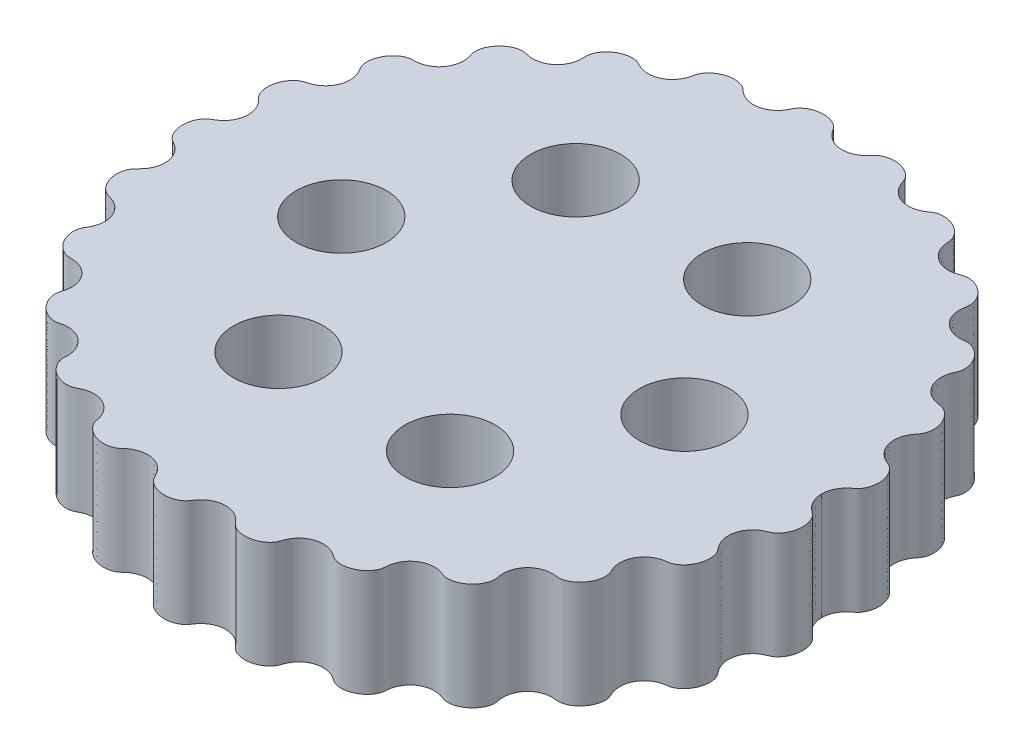
SolidWorks part; units mm, degrees
ref_plane "Front Plane" through (0, 0, 0) normal (0, 0, 1) x (1, 0, 0)
ref_plane "Top Plane" through (0, 0, 0) normal (0, 1, 0) x (1, 0, 0)
ref_plane "Right Plane" through (0, 0, 0) normal (1, 0, 0) x (0, 0, -1)
sketch "Sketch4" plane through (0, 0, 0) normal (0, 1, 0) x (1, 0, 0)
  line L0 (-15.4, 0) -> (14.4, 0) construction
  line L1 (0, 0) -> (0, -14.9128) construction
  line L2 (0, 0) -> (0, 14.9128) construction
  line L3 (-0.5, 0) -> (-0.5, -14.9128) construction
  line L4 (-0.5, 0) -> (-0.5, 14.9128) construction
  line L5 (14.4, 0) -> (15.5, 0) construction
  line L6 (0, 14.9128) -> (0, -14.9128) construction
  line L7 (5.9, 0) -> (9.1, 0) construction
  line L8 (5.9, 0) -> (7.5, 0)
  circle A0 centre (-0.5, 0) radius 16 construction
  circle A1 centre (15.5, 0) radius 1
  circle A2 centre (15.0351, -3.8291) radius 1
  circle A3 centre (13.6673, -7.4356) radius 1
  circle A4 centre (11.4762, -10.61) radius 1
  circle A5 centre (8.589, -13.1677) radius 1
  circle A6 centre (5.1737, -14.9603) radius 1
  circle A7 centre (1.4286, -15.8833) radius 1
  circle A8 centre (-2.4286, -15.8833) radius 1
  circle A9 centre (-6.1737, -14.9603) radius 1
  circle A10 centre (-9.589, -13.1677) radius 1
  circle A11 centre (-12.4762, -10.61) radius 1
  circle A12 centre (-14.6673, -7.4356) radius 1
  circle A13 centre (-16.0351, -3.8291) radius 1
  circle A14 centre (-16.5, 0) radius 1
  circle A15 centre (-16.0351, 3.8291) radius 1
  circle A16 centre (-14.6673, 7.4356) radius 1
  circle A17 centre (-12.4762, 10.61) radius 1
  circle A18 centre (-9.589, 13.1677) radius 1
  circle A19 centre (-6.1737, 14.9603) radius 1
  circle A20 centre (-2.4286, 15.8833) radius 1
  circle A21 centre (1.4286, 15.8833) radius 1
  circle A22 centre (5.1737, 14.9603) radius 1
  circle A23 centre (8.589, 13.1677) radius 1
  circle A24 centre (11.4762, 10.61) radius 1
  circle A25 centre (13.6673, 7.4356) radius 1
  circle A26 centre (15.0351, 3.8291) radius 1
  circle A27 centre (0, 0) radius 8
  circle A28 centre (8, 0) radius 2.1
  circle A29 centre (4, 6.9282) radius 2.1
  circle A30 centre (-4, 6.9282) radius 2.1
  circle A31 centre (-8, 0) radius 2.1
  circle A32 centre (-4, -6.9282) radius 2.1
  circle A33 centre (4, -6.9282) radius 2.1
  circle A34 centre (-1, 0) radius 8 construction
  circle A35 centre (3, -6.9282) radius 2.1
  circle A36 centre (-5, -6.9282) radius 2.1
  circle A37 centre (-9, 0) radius 2.1
  circle A38 centre (-5, 6.9282) radius 2.1
  circle A39 centre (3, 6.9282) radius 2.1
  circle A40 centre (7, 0) radius 2.1
  circle A41 centre (7.5, 0) radius 1.5
  circle A42 centre (3.5, -6.9282) radius 1.5
  circle A43 centre (-4.5, -6.9282) radius 1.5
  circle A44 centre (-8.5, 0) radius 1.5
  circle A45 centre (-4.5, 6.9282) radius 1.5
  circle A46 centre (3.5, 6.9282) radius 1.5
  spline S0 degree 4 poles (14.1521, 3.1658) (14.188, 3.1199) (14.2658, 3.0332) (14.3775, 2.9384) (14.515, 2.8555) (14.6203, 2.806) (14.6874, 2.778) (14.7412, 2.7556) (14.7939, 2.7309) (14.8442, 2.7016) (14.9616, 2.6171) (15.116, 2.4418) (15.2531, 2.163) (15.3044, 1.8261) (15.2781, 1.5454) (15.2134, 1.3341) (15.1457, 1.199) (15.0717, 1.0959) (14.999, 1.0246) (14.9346, 0.9749) (14.8529, 0.9144) (14.7598, 0.8351) (14.6613, 0.7318) (14.5658, 0.5985) (14.4899, 0.4547) (14.4445, 0.3242) (14.4198, 0.2202) (14.4058, 0.1237) (14.3997, 0.036) (14.399, -0.0233) (14.4055, -0.1232) (14.4175, -0.2057) (14.4353, -0.2848) (14.4589, -0.3638) (14.4955, -0.4601) (14.5538, -0.5777) (14.629, -0.6905) (14.7205, -0.7952) (14.8099, -0.8785) (14.886, -0.9397) (14.9653, -0.9969) (15.0394, -1.0608) (15.1018, -1.1365) (15.1543, -1.2193) (15.2086, -1.3292) (15.2563, -1.4688) (15.2881, -1.6381) (15.2945, -1.881) (15.2523, -2.1199) (15.1638, -2.3444) (15.0424, -2.5231) (14.9425, -2.6287) (14.8453, -2.7036) (14.7572, -2.7504) (14.6644, -2.7867) (14.5734, -2.827) (14.4636, -2.8857) (14.309, -2.9902) (14.1305, -3.1658) (13.9721, -3.435) (13.894, -3.7733) (13.9169, -4.0803) (13.9952, -4.3102) (14.0824, -4.4685) (14.1503, -4.5677) (14.21, -4.6429) (14.2706, -4.7176) (14.3202, -4.8002) (14.3654, -4.9109) (14.3993, -5.0496) (14.4169, -5.2624) (14.3843, -5.5009) (14.3041, -5.731) (14.178, -5.9418) (14.0479, -6.0957) (13.9108, -6.2086) (13.7771, -6.2844) (13.6546, -6.3259) (13.5506, -6.3413) (13.4467, -6.3556) (13.3441, -6.3782) (13.2186, -6.4164) (13.0491, -6.4902) (12.8504, -6.6239) (12.6494, -6.8484) (12.5061, -7.1523) (12.463, -7.451) (12.49, -7.6921) (12.5392, -7.8624) (12.5803, -7.968) (12.6183, -8.0504) (12.6544, -8.1336) (12.6783, -8.2214) (12.6929, -8.336) (12.6907, -8.4762) (12.6543, -8.6855) (12.5452, -8.9512) (12.3731, -9.1837) (12.1492, -9.3663) (11.9533, -9.4633) (11.8116, -9.5062) (11.6867, -9.5225) (11.5835, -9.517) (11.4812, -9.5034) (11.3782, -9.4969) (11.2749, -9.4982) (11.1721, -9.508) (11.0085, -9.5382) (10.791, -9.6158) (10.5438, -9.7787) (10.3474, -10.0243) (10.2402, -10.2686) (10.1943, -10.4842) (10.1853, -10.6384) (10.1931, -10.7705) (10.2091, -10.8795) (10.2256, -10.9662) (10.236, -11.0539) (10.2331, -11.1423) (10.2158, -11.2534) (10.1767, -11.3842) (10.0886, -11.5718) (9.9146, -11.8006) (9.6439, -12.0158) (9.3384, -12.1314) (9.0923, -12.1519) (8.9388, -12.1247) (8.8741, -12.1049) (8.8233, -12.0863) (8.76, -12.0622) (8.6577, -12.0268) (8.5127, -11.9913) (8.2954, -11.971) (8.0233, -12.0058) (7.7397, -12.12) (7.4775, -12.3303) (7.3093, -12.5758) (7.2277, -12.7964) (7.1948, -12.9647) (7.1831, -13.0729) (7.1774, -13.16) (7.1639, -13.2682) (7.1207, -13.3961) (7.0432, -13.5357) (6.8963, -13.7154) (6.6678, -13.8963) (6.3478, -14.0387) (6.02, -14.0727) (5.7619, -14.0269) (5.5985, -13.9438) (5.5126, -13.8801) (5.4018, -13.8057) (5.2599, -13.7303) (5.0524, -13.6565) (4.7738, -13.623) (4.4626, -13.6683) (4.1888, -13.7999) (3.9912, -13.9665) (3.8578, -14.1339) (3.7826, -14.2632) (3.7309, -14.3799) (3.6959, -14.48) (3.6689, -14.5606) (3.6251, -14.6573) (3.5494, -14.7647) (3.44, -14.8752) (3.2557, -15.006) (2.9928, -15.1201) (2.6515, -15.1757) (2.3406, -15.1291) (2.1258, -15.0338) (2.011, -14.9468) (1.9698, -14.909) (1.9317, -14.8681) (1.8954, -14.8255) (1.8499, -14.7726) (1.7735, -14.691) (1.6576, -14.5893) (1.4677, -14.4687) (1.2013, -14.3748) (0.8943, -14.3518) (0.5705, -14.4236) (0.3173, -14.5632) (0.1515, -14.7141) (0.0481, -14.8418) (-0.0114, -14.9289) (-0.057, -15.0001) (-0.1205, -15.0845) (-0.2167, -15.1711) (-0.3455, -15.2521) (-0.5484, -15.3356) (-0.8128, -15.3854) (-1.084, -15.3726) (-1.345, -15.2972) (-1.5435, -15.1922) (-1.6658, -15.0976) (-1.7547, -15.002) (-1.8112, -14.9128) (-1.8483, -14.8369) (-1.8948, -14.7422) (-1.9811, -14.5964) (-2.1305, -14.4153) (-2.3717, -14.2374) (-2.6941, -14.1243) (-3.0058, -14.1121) (-3.2798, -14.1742) (-3.4814, -14.2713) (-3.6077, -14.3581) (-3.6929, -14.4296) (-3.7443, -14.4763) (-3.7855, -14.5136) (-3.839, -14.5578) (-3.9718, -14.6426) (-4.2092, -14.7163) (-4.5379, -14.7232) (-4.871, -14.6233) (-5.1192, -14.4741) (-5.2872, -14.3161) (-5.3818, -14.1888) (-5.4416, -14.0686) (-5.4698, -13.9639) (-5.4862, -13.8788) (-5.5106, -13.7734) (-5.5628, -13.6112) (-5.6686, -13.4029) (-5.8615, -13.1808) (-6.1409, -13.0036) (-6.4324, -12.9205) (-6.707, -12.9139) (-6.9246, -12.958) (-7.0705, -13.0119) (-7.1719, -13.0612) (-7.2342, -13.0943) (-7.2842, -13.1203) (-7.3485, -13.1494) (-7.4504, -13.1813) (-7.5929, -13.1993) (-7.8225, -13.1875) (-8.1082, -13.1019) (-8.3607, -12.9481) (-8.5641, -12.7393) (-8.6869, -12.541) (-8.7459, -12.3913) (-8.7711, -12.2579) (-8.7697, -12.1482) (-8.7645, -12.0606) (-8.7633, -11.951) (-8.7731, -11.8212) (-8.8019, -11.6732) (-8.8729, -11.4717) (-9.0045, -11.25) (-9.2205, -11.0351) (-9.4997, -10.8905) (-9.7475, -10.8369) (-9.9383, -10.8322) (-10.0675, -10.8437) (-10.1698, -10.8609) (-10.2704, -10.8859) (-10.3717, -10.9089) (-10.4995, -10.9144) (-10.6499, -10.893) (-10.8644, -10.8236) (-11.1154, -10.6702) (-11.3185, -10.4608) (-11.4614, -10.2119) (-11.5248, -10.0134) (-11.5464, -9.8777) (-11.5487, -9.7646) (-11.5393, -9.6761) (-11.5169, -9.5902) (-11.4896, -9.5058) (-11.4606, -9.3988) (-11.4371, -9.2678) (-11.428, -9.1126) (-11.4489, -8.8917) (-11.5253, -8.6444) (-11.6806, -8.3917) (-11.9083, -8.1893) (-12.1461, -8.0664) (-12.3515, -8.0112) (-12.509, -7.9918) (-12.6408, -7.9895) (-12.7466, -7.9882) (-12.8744, -7.9638) (-13.0178, -7.9059) (-13.1692, -7.8114) (-13.319, -7.6747) (-13.472, -7.4805) (-13.5815, -7.2609) (-13.644, -7.0266) (-13.6529, -6.8129) (-13.6365, -6.6729) (-13.6064, -6.5605) (-13.5704, -6.4764) (-13.5232, -6.3982) (-13.4752, -6.3206) (-13.4215, -6.2199) (-13.3522, -6.0556) (-13.2972, -5.8178) (-13.3061, -5.5112) (-13.4183, -5.1858) (-13.5996, -4.9373) (-13.7884, -4.7826) (-13.9504, -4.6931) (-14.068, -4.6441) (-14.1647, -4.6121) (-14.2634, -4.587) (-14.3606, -4.5562) (-14.4721, -4.4972) (-14.5906, -4.4054) (-14.7415, -4.2409) (-14.8856, -3.984) (-14.9605, -3.7) (-14.9625, -3.4094) (-14.9171, -3.1994) (-14.8649, -3.0656) (-14.8048, -2.9613) (-14.7437, -2.886) (-14.6735, -2.8194) (-14.6048, -2.7515) (-14.5411, -2.6786) (-14.4829, -2.6013) (-14.3984, -2.4684) (-14.3099, -2.2678) (-14.2572, -1.9916) (-14.2948, -1.6527) (-14.4157, -1.3725) (-14.5648, -1.1806) (-14.7009, -1.0585) (-14.8015, -0.9857) (-14.886, -0.9336) (-14.9732, -0.8861) (-15.056, -0.8309) (-15.1453, -0.7457) (-15.2341, -0.6279) (-15.3021, -0.4979) (-15.3506, -0.3595) (-15.3784, -0.2422) (-15.3932, -0.1473) (-15.4005, -0.038) (-15.4007, 0.0312) (-15.3943, 0.133) (-15.3819, 0.2227) (-15.3632, 0.3082) (-15.3383, 0.3938) (-15.2991, 0.498) (-15.241, 0.614) (-15.1569, 0.7356) (-15.0521, 0.8388) (-14.947, 0.9) (-14.8417, 0.9596) (-14.7374, 1.0292) (-14.6222, 1.1253) (-14.4762, 1.2888) (-14.3483, 1.5104) (-14.2696, 1.788) (-14.2718, 2.0824) (-14.3338, 2.3297) (-14.4228, 2.5131) (-14.5089, 2.6398) (-14.5912, 2.7371) (-14.6628, 2.8095) (-14.7315, 2.8736) (-14.7874, 2.9388) (-14.8392, 3.0187) (-14.9, 3.1445) (-14.933, 3.2628) (-14.9484, 3.3663) (-14.9531, 3.4358) knots 0 0 0 0 0 0.003662 0.007324 0.009155 0.010071 0.010986 0.011902 0.012818 0.013733 0.014649 0.020984 0.02732 0.032959 0.035778 0.038598 0.041156 0.042436 0.043715 0.044995 0.046274 0.048833 0.051398 0.053964 0.05653 0.059096 0.059963 0.060831 0.062566 0.06386 0.065154 0.066448 0.067743 0.069037 0.070331 0.072919 0.075992 0.077529 0.079065 0.080602 0.082139 0.083675 0.085212 0.086754 0.088296 0.09138 0.094464 0.097548 0.103529 0.106519 0.10951 0.111075 0.112641 0.114207 0.115773 0.117339 0.118905 0.122036 0.127492 0.132948 0.138255 0.143562 0.146585 0.148096 0.149608 0.151119 0.15263 0.154142 0.155653 0.158618 0.161583 0.167513 0.170668 0.173824 0.176979 0.180135 0.181785 0.183435 0.185086 0.186736 0.188387 0.190037 0.193338 0.198334 0.203329 0.208757 0.214186 0.217039 0.218465 0.219892 0.221319 0.222745 0.224172 0.225598 0.228568 0.231538 0.237477 0.243509 0.246525 0.249541 0.251164 0.252787 0.25441 0.256033 0.257656 0.259279 0.260902 0.262525 0.268116 0.273708 0.279232 0.281995 0.284757 0.287531 0.288919 0.290306 0.291693 0.293081 0.294468 0.295855 0.298752 0.301648 0.307441 0.313806 0.320171 0.321875 0.322726 0.323578 0.32443 0.325282 0.326985 0.330392 0.333799 0.338942 0.344084 0.349371 0.354658 0.3574 0.358771 0.360142 0.361513 0.362884 0.365627 0.368572 0.371516 0.377406 0.383828 0.390249 0.39193 0.393611 0.395291 0.396972 0.400333 0.403695 0.409076 0.414457 0.419833 0.422521 0.425209 0.427878 0.429213 0.430548 0.431883 0.433218 0.435887 0.438758 0.441629 0.44737 0.453781 0.460191 0.46107 0.46195 0.462829 0.463708 0.464587 0.465466 0.467225 0.470742 0.474259 0.479542 0.484825 0.489836 0.494847 0.497504 0.498832 0.500161 0.501489 0.502818 0.505475 0.508247 0.51102 0.516564 0.52227 0.525123 0.527976 0.530631 0.531959 0.533286 0.534614 0.535941 0.538597 0.543936 0.549276 0.554531 0.559787 0.563284 0.566782 0.568531 0.569405 0.570279 0.571154 0.572028 0.573777 0.580153 0.586529 0.592383 0.595311 0.598238 0.600963 0.602326 0.603688 0.605051 0.606414 0.609139 0.614393 0.619646 0.62466 0.629675 0.633224 0.636772 0.638547 0.639434 0.640321 0.641208 0.642095 0.64387 0.647026 0.650182 0.656494 0.66242 0.665383 0.668345 0.671105 0.672484 0.673864 0.675243 0.676623 0.679382 0.682041 0.684701 0.690021 0.695473 0.700926 0.704188 0.705819 0.70745 0.709081 0.710712 0.712344 0.713975 0.717095 0.720216 0.726458 0.732287 0.735201 0.738116 0.739511 0.740907 0.742302 0.743698 0.745093 0.746488 0.749279 0.752059 0.754839 0.760398 0.765424 0.770449 0.773769 0.777088 0.778748 0.780408 0.782068 0.783727 0.786901 0.790075 0.793249 0.796422 0.802397 0.805385 0.808372 0.809808 0.811244 0.812679 0.814115 0.81555 0.816986 0.819857 0.825318 0.830779 0.83599 0.841201 0.844404 0.846006 0.847607 0.849209 0.850811 0.852412 0.854014 0.857107 0.8602 0.866387 0.872353 0.875336 0.878319 0.87984 0.881361 0.882882 0.884402 0.885923 0.887444 0.888965 0.890486 0.895823 0.90116 0.906397 0.911634 0.914757 0.916319 0.91788 0.919441 0.921003 0.922564 0.924126 0.927182 0.930238 0.931767 0.933295 0.934823 0.936351 0.937751 0.93915 0.940549 0.941949 0.943348 0.944747 0.947546 0.950087 0.952628 0.953898 0.955168 0.957709 0.960509 0.96331 0.96891 0.973663 0.978415 0.981621 0.984826 0.986428 0.988031 0.989634 0.991236 0.992332 0.993427 0.995618 1 1 1 1 1 construction
  spline S1 degree 4 poles (14.4, 0) (14.4, -0.018) (14.401, -0.0542) (14.4055, -0.1232) (14.4175, -0.2057) (14.4353, -0.2848) (14.4589, -0.3638) (14.4955, -0.4601) (14.5538, -0.5777) (14.629, -0.6905) (14.7205, -0.7952) (14.8099, -0.8785) (14.886, -0.9397) (14.9653, -0.9969) (15.0394, -1.0608) (15.1018, -1.1365) (15.1543, -1.2193) (15.2086, -1.3292) (15.2563, -1.4688) (15.2881, -1.6381) (15.2945, -1.881) (15.2523, -2.1199) (15.1638, -2.3444) (15.0424, -2.5231) (14.9425, -2.6287) (14.8453, -2.7036) (14.7572, -2.7504) (14.6644, -2.7867) (14.5734, -2.827) (14.4636, -2.8857) (14.309, -2.9902) (14.1305, -3.1658) (13.9721, -3.435) (13.894, -3.7733) (13.9169, -4.0803) (13.9952, -4.3102) (14.0824, -4.4685) (14.1503, -4.5677) (14.21, -4.6429) (14.2706, -4.7176) (14.3202, -4.8002) (14.3654, -4.9109) (14.3993, -5.0496) (14.4169, -5.2624) (14.3843, -5.5009) (14.3041, -5.731) (14.178, -5.9418) (14.0479, -6.0957) (13.9108, -6.2086) (13.7771, -6.2844) (13.6546, -6.3259) (13.5506, -6.3413) (13.4467, -6.3556) (13.3441, -6.3782) (13.2186, -6.4164) (13.0491, -6.4902) (12.8504, -6.6239) (12.6494, -6.8484) (12.5061, -7.1523) (12.463, -7.451) (12.49, -7.6921) (12.5392, -7.8624) (12.5803, -7.968) (12.6183, -8.0504) (12.6544, -8.1336) (12.6783, -8.2214) (12.6929, -8.336) (12.6907, -8.4762) (12.6543, -8.6855) (12.5452, -8.9512) (12.3731, -9.1837) (12.1492, -9.3663) (11.9533, -9.4633) (11.8116, -9.5062) (11.6867, -9.5225) (11.5835, -9.517) (11.4812, -9.5034) (11.3782, -9.4969) (11.2749, -9.4982) (11.1721, -9.508) (11.0085, -9.5382) (10.791, -9.6158) (10.5438, -9.7787) (10.3474, -10.0243) (10.2402, -10.2686) (10.1943, -10.4842) (10.1853, -10.6384) (10.1931, -10.7705) (10.2091, -10.8795) (10.2256, -10.9662) (10.236, -11.0539) (10.2331, -11.1423) (10.2158, -11.2534) (10.1767, -11.3842) (10.0886, -11.5718) (9.9146, -11.8006) (9.6439, -12.0158) (9.3384, -12.1314) (9.0923, -12.1519) (8.9388, -12.1247) (8.8741, -12.1049) (8.8233, -12.0863) (8.76, -12.0622) (8.6577, -12.0268) (8.5127, -11.9913) (8.2954, -11.971) (8.0233, -12.0058) (7.7397, -12.12) (7.4775, -12.3303) (7.3093, -12.5758) (7.2277, -12.7964) (7.1948, -12.9647) (7.1831, -13.0729) (7.1774, -13.16) (7.1639, -13.2682) (7.1207, -13.3961) (7.0432, -13.5357) (6.8963, -13.7154) (6.6678, -13.8963) (6.3478, -14.0387) (6.02, -14.0727) (5.7619, -14.0269) (5.5985, -13.9438) (5.5126, -13.8801) (5.4018, -13.8057) (5.2599, -13.7303) (5.0524, -13.6565) (4.7738, -13.623) (4.4626, -13.6683) (4.1888, -13.7999) (3.9912, -13.9665) (3.8578, -14.1339) (3.7826, -14.2632) (3.7309, -14.3799) (3.6959, -14.48) (3.6689, -14.5606) (3.6251, -14.6573) (3.5494, -14.7647) (3.44, -14.8752) (3.2557, -15.006) (2.9928, -15.1201) (2.6515, -15.1757) (2.3406, -15.1291) (2.1258, -15.0338) (2.011, -14.9468) (1.9698, -14.909) (1.9317, -14.8681) (1.8954, -14.8255) (1.8499, -14.7726) (1.7735, -14.691) (1.6576, -14.5893) (1.4677, -14.4687) (1.2013, -14.3748) (0.8943, -14.3518) (0.5705, -14.4236) (0.3173, -14.5632) (0.1515, -14.7141) (0.0481, -14.8418) (-0.0114, -14.9289) (-0.057, -15.0001) (-0.1205, -15.0845) (-0.2167, -15.1711) (-0.3455, -15.2521) (-0.5484, -15.3356) (-0.8128, -15.3854) (-1.084, -15.3726) (-1.345, -15.2972) (-1.5435, -15.1922) (-1.6658, -15.0976) (-1.7547, -15.002) (-1.8112, -14.9128) (-1.8483, -14.8369) (-1.8948, -14.7422) (-1.9811, -14.5964) (-2.1305, -14.4153) (-2.3717, -14.2374) (-2.6941, -14.1243) (-3.0058, -14.1121) (-3.2798, -14.1742) (-3.4814, -14.2713) (-3.6077, -14.3581) (-3.6929, -14.4296) (-3.7443, -14.4763) (-3.7855, -14.5136) (-3.839, -14.5578) (-3.9718, -14.6426) (-4.2092, -14.7163) (-4.5379, -14.7232) (-4.871, -14.6233) (-5.1192, -14.4741) (-5.2872, -14.3161) (-5.3818, -14.1888) (-5.4416, -14.0686) (-5.4698, -13.9639) (-5.4862, -13.8788) (-5.5106, -13.7734) (-5.5628, -13.6112) (-5.6686, -13.4029) (-5.8615, -13.1808) (-6.1409, -13.0036) (-6.4324, -12.9205) (-6.707, -12.9139) (-6.9246, -12.958) (-7.0705, -13.0119) (-7.1719, -13.0612) (-7.2342, -13.0943) (-7.2842, -13.1203) (-7.3485, -13.1494) (-7.4504, -13.1813) (-7.5929, -13.1993) (-7.8225, -13.1875) (-8.1082, -13.1019) (-8.3607, -12.9481) (-8.5641, -12.7393) (-8.6869, -12.541) (-8.7459, -12.3913) (-8.7711, -12.2579) (-8.7697, -12.1482) (-8.7645, -12.0606) (-8.7633, -11.951) (-8.7731, -11.8212) (-8.8019, -11.6732) (-8.8729, -11.4717) (-9.0045, -11.25) (-9.2205, -11.0351) (-9.4997, -10.8905) (-9.7475, -10.8369) (-9.9383, -10.8322) (-10.0675, -10.8437) (-10.1698, -10.8609) (-10.2704, -10.8859) (-10.3717, -10.9089) (-10.4995, -10.9144) (-10.6499, -10.893) (-10.8644, -10.8236) (-11.1154, -10.6702) (-11.3185, -10.4608) (-11.4614, -10.2119) (-11.5248, -10.0134) (-11.5464, -9.8777) (-11.5487, -9.7646) (-11.5393, -9.6761) (-11.5169, -9.5902) (-11.4896, -9.5058) (-11.4606, -9.3988) (-11.4371, -9.2678) (-11.428, -9.1126) (-11.4489, -8.8917) (-11.5253, -8.6444) (-11.6806, -8.3917) (-11.9083, -8.1893) (-12.1461, -8.0664) (-12.3515, -8.0112) (-12.509, -7.9918) (-12.6408, -7.9895) (-12.7466, -7.9882) (-12.8744, -7.9638) (-13.0178, -7.9059) (-13.1692, -7.8114) (-13.319, -7.6747) (-13.472, -7.4805) (-13.5815, -7.2609) (-13.644, -7.0266) (-13.6529, -6.8129) (-13.6365, -6.6729) (-13.6064, -6.5605) (-13.5704, -6.4764) (-13.5232, -6.3982) (-13.4752, -6.3206) (-13.4215, -6.2199) (-13.3522, -6.0556) (-13.2972, -5.8178) (-13.3061, -5.5112) (-13.4183, -5.1858) (-13.5996, -4.9373) (-13.7884, -4.7826) (-13.9504, -4.6931) (-14.068, -4.6441) (-14.1647, -4.6121) (-14.2634, -4.587) (-14.3606, -4.5562) (-14.4721, -4.4972) (-14.5906, -4.4054) (-14.7415, -4.2409) (-14.8856, -3.984) (-14.9605, -3.7) (-14.9625, -3.4094) (-14.9171, -3.1994) (-14.8649, -3.0656) (-14.8048, -2.9613) (-14.7437, -2.886) (-14.6735, -2.8194) (-14.6048, -2.7515) (-14.5411, -2.6786) (-14.4829, -2.6013) (-14.3984, -2.4684) (-14.3099, -2.2678) (-14.2572, -1.9916) (-14.2948, -1.6527) (-14.4157, -1.3725) (-14.5648, -1.1806) (-14.7009, -1.0585) (-14.8015, -0.9857) (-14.886, -0.9336) (-14.9732, -0.8861) (-15.056, -0.8309) (-15.1453, -0.7457) (-15.2341, -0.6279) (-15.3021, -0.4979) (-15.3506, -0.3595) (-15.3784, -0.2422) (-15.3932, -0.1473) (-15.3988, -0.0635) (-15.4, -0.0212) (-15.4, 0) knots 0.062566 0.062566 0.062566 0.062566 0.062566 0.06386 0.065154 0.066448 0.067743 0.069037 0.070331 0.072919 0.075992 0.077529 0.079065 0.080602 0.082139 0.083675 0.085212 0.086754 0.088296 0.09138 0.094464 0.097548 0.103529 0.106519 0.10951 0.111075 0.112641 0.114207 0.115773 0.117339 0.118905 0.122036 0.127492 0.132948 0.138255 0.143562 0.146585 0.148096 0.149608 0.151119 0.15263 0.154142 0.155653 0.158618 0.161583 0.167513 0.170668 0.173824 0.176979 0.180135 0.181785 0.183435 0.185086 0.186736 0.188387 0.190037 0.193338 0.198334 0.203329 0.208757 0.214186 0.217039 0.218465 0.219892 0.221319 0.222745 0.224172 0.225598 0.228568 0.231538 0.237477 0.243509 0.246525 0.249541 0.251164 0.252787 0.25441 0.256033 0.257656 0.259279 0.260902 0.262525 0.268116 0.273708 0.279232 0.281995 0.284757 0.287531 0.288919 0.290306 0.291693 0.293081 0.294468 0.295855 0.298752 0.301648 0.307441 0.313806 0.320171 0.321875 0.322726 0.323578 0.32443 0.325282 0.326985 0.330392 0.333799 0.338942 0.344084 0.349371 0.354658 0.3574 0.358771 0.360142 0.361513 0.362884 0.365627 0.368572 0.371516 0.377406 0.383828 0.390249 0.39193 0.393611 0.395291 0.396972 0.400333 0.403695 0.409076 0.414457 0.419833 0.422521 0.425209 0.427878 0.429213 0.430548 0.431883 0.433218 0.435887 0.438758 0.441629 0.44737 0.453781 0.460191 0.46107 0.46195 0.462829 0.463708 0.464587 0.465466 0.467225 0.470742 0.474259 0.479542 0.484825 0.489836 0.494847 0.497504 0.498832 0.500161 0.501489 0.502818 0.505475 0.508247 0.51102 0.516564 0.52227 0.525123 0.527976 0.530631 0.531959 0.533286 0.534614 0.535941 0.538597 0.543936 0.549276 0.554531 0.559787 0.563284 0.566782 0.568531 0.569405 0.570279 0.571154 0.572028 0.573777 0.580153 0.586529 0.592383 0.595311 0.598238 0.600963 0.602326 0.603688 0.605051 0.606414 0.609139 0.614393 0.619646 0.62466 0.629675 0.633224 0.636772 0.638547 0.639434 0.640321 0.641208 0.642095 0.64387 0.647026 0.650182 0.656494 0.66242 0.665383 0.668345 0.671105 0.672484 0.673864 0.675243 0.676623 0.679382 0.682041 0.684701 0.690021 0.695473 0.700926 0.704188 0.705819 0.70745 0.709081 0.710712 0.712344 0.713975 0.717095 0.720216 0.726458 0.732287 0.735201 0.738116 0.739511 0.740907 0.742302 0.743698 0.745093 0.746488 0.749279 0.752059 0.754839 0.760398 0.765424 0.770449 0.773769 0.777088 0.778748 0.780408 0.782068 0.783727 0.786901 0.790075 0.793249 0.796422 0.802397 0.805385 0.808372 0.809808 0.811244 0.812679 0.814115 0.81555 0.816986 0.819857 0.825318 0.830779 0.83599 0.841201 0.844404 0.846006 0.847607 0.849209 0.850811 0.852412 0.854014 0.857107 0.8602 0.866387 0.872353 0.875336 0.878319 0.87984 0.881361 0.882882 0.884402 0.885923 0.887444 0.888965 0.890486 0.895823 0.90116 0.906397 0.911634 0.914757 0.916319 0.91788 0.919441 0.921003 0.922564 0.924126 0.927182 0.930238 0.931767 0.933295 0.934823 0.936351 0.936351 0.936351 0.936351 0.936351
  spline S2 degree 4 poles (14.4, 0) (14.4, 0.018) (14.401, 0.0542) (14.4055, 0.1232) (14.4175, 0.2057) (14.4353, 0.2848) (14.4589, 0.3638) (14.4955, 0.4601) (14.5538, 0.5777) (14.629, 0.6905) (14.7205, 0.7952) (14.8099, 0.8785) (14.886, 0.9397) (14.9653, 0.9969) (15.0394, 1.0608) (15.1018, 1.1365) (15.1543, 1.2193) (15.2086, 1.3292) (15.2563, 1.4688) (15.2881, 1.6381) (15.2945, 1.881) (15.2523, 2.1199) (15.1638, 2.3444) (15.0424, 2.5231) (14.9425, 2.6287) (14.8453, 2.7036) (14.7572, 2.7504) (14.6644, 2.7867) (14.5734, 2.827) (14.4636, 2.8857) (14.309, 2.9902) (14.1305, 3.1658) (13.9721, 3.435) (13.894, 3.7733) (13.9169, 4.0803) (13.9952, 4.3102) (14.0824, 4.4685) (14.1503, 4.5677) (14.21, 4.6429) (14.2706, 4.7176) (14.3202, 4.8002) (14.3654, 4.9109) (14.3993, 5.0496) (14.4169, 5.2624) (14.3843, 5.5009) (14.3041, 5.731) (14.178, 5.9418) (14.0479, 6.0957) (13.9108, 6.2086) (13.7771, 6.2844) (13.6546, 6.3259) (13.5506, 6.3413) (13.4467, 6.3556) (13.3441, 6.3782) (13.2186, 6.4164) (13.0491, 6.4902) (12.8504, 6.6239) (12.6494, 6.8484) (12.5061, 7.1523) (12.463, 7.451) (12.49, 7.6921) (12.5392, 7.8624) (12.5803, 7.968) (12.6183, 8.0504) (12.6544, 8.1336) (12.6783, 8.2214) (12.6929, 8.336) (12.6907, 8.4762) (12.6543, 8.6855) (12.5452, 8.9512) (12.3731, 9.1837) (12.1492, 9.3663) (11.9533, 9.4633) (11.8116, 9.5062) (11.6867, 9.5225) (11.5835, 9.517) (11.4812, 9.5034) (11.3782, 9.4969) (11.2749, 9.4982) (11.1721, 9.508) (11.0085, 9.5382) (10.791, 9.6158) (10.5438, 9.7787) (10.3474, 10.0243) (10.2402, 10.2686) (10.1943, 10.4842) (10.1853, 10.6384) (10.1931, 10.7705) (10.2091, 10.8795) (10.2256, 10.9662) (10.236, 11.0539) (10.2331, 11.1423) (10.2158, 11.2534) (10.1767, 11.3842) (10.0886, 11.5718) (9.9146, 11.8006) (9.6439, 12.0158) (9.3384, 12.1314) (9.0923, 12.1519) (8.9388, 12.1247) (8.8741, 12.1049) (8.8233, 12.0863) (8.76, 12.0622) (8.6577, 12.0268) (8.5127, 11.9913) (8.2954, 11.971) (8.0233, 12.0058) (7.7397, 12.12) (7.4775, 12.3303) (7.3093, 12.5758) (7.2277, 12.7964) (7.1948, 12.9647) (7.1831, 13.0729) (7.1774, 13.16) (7.1639, 13.2682) (7.1207, 13.3961) (7.0432, 13.5357) (6.8963, 13.7154) (6.6678, 13.8963) (6.3478, 14.0387) (6.02, 14.0727) (5.7619, 14.0269) (5.5985, 13.9438) (5.5126, 13.8801) (5.4018, 13.8057) (5.2599, 13.7303) (5.0524, 13.6565) (4.7738, 13.623) (4.4626, 13.6683) (4.1888, 13.7999) (3.9912, 13.9665) (3.8578, 14.1339) (3.7826, 14.2632) (3.7309, 14.3799) (3.6959, 14.48) (3.6689, 14.5606) (3.6251, 14.6573) (3.5494, 14.7647) (3.44, 14.8752) (3.2557, 15.006) (2.9928, 15.1201) (2.6515, 15.1757) (2.3406, 15.1291) (2.1258, 15.0338) (2.011, 14.9468) (1.9698, 14.909) (1.9317, 14.8681) (1.8954, 14.8255) (1.8499, 14.7726) (1.7735, 14.691) (1.6576, 14.5893) (1.4677, 14.4687) (1.2013, 14.3748) (0.8943, 14.3518) (0.5705, 14.4236) (0.3173, 14.5632) (0.1515, 14.7141) (0.0481, 14.8418) (-0.0114, 14.9289) (-0.057, 15) (-0.1205, 15.0845) (-0.2167, 15.1711) (-0.3455, 15.2521) (-0.5484, 15.3356) (-0.8128, 15.3854) (-1.084, 15.3726) (-1.345, 15.2972) (-1.5435, 15.1922) (-1.6658, 15.0976) (-1.7547, 15.002) (-1.8112, 14.9128) (-1.8483, 14.8369) (-1.8948, 14.7422) (-1.9811, 14.5964) (-2.1305, 14.4153) (-2.3717, 14.2374) (-2.6941, 14.1243) (-3.0058, 14.1121) (-3.2798, 14.1742) (-3.4814, 14.2713) (-3.6077, 14.3581) (-3.6929, 14.4296) (-3.7443, 14.4763) (-3.7855, 14.5136) (-3.839, 14.5578) (-3.9718, 14.6426) (-4.2092, 14.7163) (-4.5379, 14.7232) (-4.871, 14.6233) (-5.1192, 14.4741) (-5.2872, 14.3161) (-5.3818, 14.1887) (-5.4416, 14.0686) (-5.4698, 13.9639) (-5.4862, 13.8788) (-5.5106, 13.7734) (-5.5628, 13.6112) (-5.6686, 13.4029) (-5.8615, 13.1808) (-6.1409, 13.0036) (-6.4324, 12.9205) (-6.707, 12.9139) (-6.9246, 12.958) (-7.0705, 13.0119) (-7.1719, 13.0612) (-7.2342, 13.0943) (-7.2842, 13.1203) (-7.3485, 13.1494) (-7.4504, 13.1813) (-7.5929, 13.1993) (-7.8225, 13.1875) (-8.1082, 13.1019) (-8.3607, 12.9481) (-8.5641, 12.7393) (-8.6869, 12.541) (-8.7459, 12.3913) (-8.7711, 12.2579) (-8.7697, 12.1482) (-8.7645, 12.0606) (-8.7633, 11.951) (-8.7731, 11.8212) (-8.8019, 11.6732) (-8.8729, 11.4717) (-9.0045, 11.25) (-9.2205, 11.0351) (-9.4997, 10.8905) (-9.7475, 10.8369) (-9.9383, 10.8322) (-10.0675, 10.8437) (-10.1698, 10.8609) (-10.2704, 10.8859) (-10.3717, 10.9089) (-10.4995, 10.9144) (-10.6499, 10.893) (-10.8644, 10.8236) (-11.1154, 10.6702) (-11.3185, 10.4608) (-11.4614, 10.2119) (-11.5248, 10.0134) (-11.5464, 9.8777) (-11.5487, 9.7646) (-11.5393, 9.6761) (-11.5169, 9.5902) (-11.4896, 9.5058) (-11.4606, 9.3988) (-11.4371, 9.2678) (-11.428, 9.1126) (-11.4489, 8.8917) (-11.5253, 8.6444) (-11.6806, 8.3917) (-11.9083, 8.1893) (-12.1461, 8.0664) (-12.3515, 8.0112) (-12.509, 7.9918) (-12.6408, 7.9895) (-12.7466, 7.9882) (-12.8744, 7.9638) (-13.0178, 7.9059) (-13.1692, 7.8114) (-13.319, 7.6747) (-13.472, 7.4805) (-13.5815, 7.2609) (-13.644, 7.0266) (-13.6529, 6.8129) (-13.6365, 6.6728) (-13.6064, 6.5605) (-13.5704, 6.4764) (-13.5232, 6.3982) (-13.4752, 6.3206) (-13.4215, 6.2199) (-13.3522, 6.0556) (-13.2972, 5.8178) (-13.3061, 5.5112) (-13.4183, 5.1858) (-13.5996, 4.9373) (-13.7884, 4.7826) (-13.9504, 4.6931) (-14.068, 4.6441) (-14.1647, 4.6121) (-14.2634, 4.587) (-14.3606, 4.5562) (-14.4721, 4.4972) (-14.5906, 4.4054) (-14.7415, 4.2409) (-14.8856, 3.984) (-14.9605, 3.7) (-14.9625, 3.4094) (-14.9171, 3.1994) (-14.8649, 3.0655) (-14.8048, 2.9613) (-14.7437, 2.886) (-14.6735, 2.8194) (-14.6048, 2.7515) (-14.5411, 2.6786) (-14.4829, 2.6013) (-14.3984, 2.4684) (-14.3099, 2.2678) (-14.2572, 1.9916) (-14.2948, 1.6527) (-14.4157, 1.3725) (-14.5648, 1.1806) (-14.7009, 1.0585) (-14.8015, 0.9857) (-14.886, 0.9336) (-14.9732, 0.8861) (-15.056, 0.8309) (-15.1453, 0.7457) (-15.2341, 0.6279) (-15.3021, 0.4979) (-15.3506, 0.3595) (-15.3784, 0.2422) (-15.3932, 0.1473) (-15.3988, 0.0635) (-15.4, 0.0212) (-15.4, 0) knots 0.062566 0.062566 0.062566 0.062566 0.062566 0.06386 0.065154 0.066448 0.067743 0.069037 0.070331 0.072919 0.075992 0.077529 0.079065 0.080602 0.082139 0.083675 0.085212 0.086754 0.088296 0.09138 0.094464 0.097548 0.103529 0.106519 0.10951 0.111075 0.112641 0.114207 0.115773 0.117339 0.118905 0.122036 0.127492 0.132948 0.138255 0.143562 0.146585 0.148096 0.149608 0.151119 0.15263 0.154142 0.155653 0.158618 0.161583 0.167513 0.170668 0.173824 0.176979 0.180135 0.181785 0.183435 0.185086 0.186736 0.188387 0.190037 0.193338 0.198334 0.203329 0.208757 0.214186 0.217039 0.218465 0.219892 0.221319 0.222745 0.224172 0.225598 0.228568 0.231538 0.237477 0.243509 0.246525 0.249541 0.251164 0.252787 0.25441 0.256033 0.257656 0.259279 0.260902 0.262525 0.268116 0.273708 0.279232 0.281995 0.284757 0.287531 0.288919 0.290306 0.291693 0.293081 0.294468 0.295855 0.298752 0.301648 0.307441 0.313806 0.320171 0.321875 0.322726 0.323578 0.32443 0.325282 0.326985 0.330392 0.333799 0.338942 0.344084 0.349371 0.354658 0.3574 0.358771 0.360142 0.361513 0.362884 0.365627 0.368572 0.371516 0.377406 0.383828 0.390249 0.39193 0.393611 0.395291 0.396972 0.400333 0.403695 0.409076 0.414457 0.419833 0.422521 0.425209 0.427878 0.429213 0.430548 0.431883 0.433218 0.435887 0.438758 0.441629 0.44737 0.453781 0.460191 0.46107 0.46195 0.462829 0.463708 0.464587 0.465466 0.467225 0.470742 0.474259 0.479542 0.484825 0.489836 0.494847 0.497504 0.498832 0.500161 0.501489 0.502818 0.505475 0.508247 0.51102 0.516564 0.52227 0.525123 0.527976 0.530631 0.531959 0.533286 0.534614 0.535941 0.538597 0.543936 0.549276 0.554531 0.559787 0.563284 0.566782 0.568531 0.569405 0.570279 0.571154 0.572028 0.573777 0.580153 0.586529 0.592383 0.595311 0.598238 0.600963 0.602326 0.603688 0.605051 0.606414 0.609139 0.614393 0.619646 0.62466 0.629675 0.633224 0.636772 0.638547 0.639434 0.640321 0.641208 0.642095 0.64387 0.647026 0.650182 0.656494 0.66242 0.665383 0.668345 0.671105 0.672484 0.673864 0.675243 0.676623 0.679382 0.682041 0.684701 0.690021 0.695473 0.700926 0.704188 0.705819 0.70745 0.709081 0.710712 0.712344 0.713975 0.717095 0.720216 0.726458 0.732287 0.735201 0.738116 0.739511 0.740907 0.742302 0.743698 0.745093 0.746488 0.749279 0.752059 0.754839 0.760398 0.765424 0.770449 0.773769 0.777088 0.778748 0.780408 0.782068 0.783727 0.786901 0.790075 0.793249 0.796422 0.802397 0.805385 0.808372 0.809808 0.811244 0.812679 0.814115 0.81555 0.816986 0.819857 0.825318 0.830779 0.83599 0.841201 0.844404 0.846006 0.847607 0.849209 0.850811 0.852412 0.854014 0.857107 0.8602 0.866387 0.872353 0.875336 0.878319 0.87984 0.881361 0.882882 0.884402 0.885923 0.887444 0.888965 0.890486 0.895823 0.90116 0.906397 0.911634 0.914757 0.916319 0.91788 0.919441 0.921003 0.922564 0.924126 0.927182 0.930238 0.931767 0.933295 0.934823 0.936351 0.936351 0.936351 0.936351 0.936351
  spline S3 degree 4 poles (-15.4, 0) (-15.4, -0.018) (-15.401, -0.0542) (-15.4055, -0.1232) (-15.4175, -0.2057) (-15.4353, -0.2848) (-15.4589, -0.3638) (-15.4955, -0.4601) (-15.5538, -0.5777) (-15.629, -0.6905) (-15.7205, -0.7952) (-15.8099, -0.8785) (-15.886, -0.9397) (-15.9653, -0.9969) (-16.0394, -1.0608) (-16.1018, -1.1365) (-16.1543, -1.2193) (-16.2086, -1.3292) (-16.2563, -1.4688) (-16.2881, -1.6381) (-16.2945, -1.881) (-16.2523, -2.1199) (-16.1638, -2.3444) (-16.0424, -2.5231) (-15.9425, -2.6287) (-15.8453, -2.7036) (-15.7572, -2.7504) (-15.6644, -2.7867) (-15.5734, -2.827) (-15.4636, -2.8857) (-15.309, -2.9902) (-15.1305, -3.1658) (-14.9721, -3.435) (-14.894, -3.7733) (-14.9169, -4.0803) (-14.9952, -4.3102) (-15.0824, -4.4685) (-15.1503, -4.5677) (-15.21, -4.6429) (-15.2706, -4.7176) (-15.3202, -4.8002) (-15.3654, -4.9109) (-15.3993, -5.0496) (-15.4169, -5.2624) (-15.3843, -5.5009) (-15.3041, -5.731) (-15.178, -5.9418) (-15.0479, -6.0957) (-14.9108, -6.2086) (-14.7771, -6.2844) (-14.6546, -6.3259) (-14.5506, -6.3413) (-14.4467, -6.3556) (-14.3441, -6.3782) (-14.2186, -6.4164) (-14.0491, -6.4902) (-13.8504, -6.6239) (-13.6494, -6.8484) (-13.5061, -7.1523) (-13.463, -7.451) (-13.49, -7.6921) (-13.5392, -7.8624) (-13.5803, -7.968) (-13.6183, -8.0504) (-13.6544, -8.1336) (-13.6783, -8.2214) (-13.6929, -8.336) (-13.6907, -8.4762) (-13.6543, -8.6855) (-13.5452, -8.9512) (-13.3731, -9.1837) (-13.1492, -9.3663) (-12.9533, -9.4633) (-12.8116, -9.5062) (-12.6867, -9.5225) (-12.5835, -9.517) (-12.4812, -9.5034) (-12.3782, -9.4969) (-12.2749, -9.4982) (-12.1721, -9.508) (-12.0085, -9.5382) (-11.791, -9.6158) (-11.5438, -9.7787) (-11.3474, -10.0243) (-11.2402, -10.2686) (-11.1943, -10.4842) (-11.1853, -10.6384) (-11.1931, -10.7705) (-11.2091, -10.8795) (-11.2256, -10.9662) (-11.236, -11.0539) (-11.2331, -11.1423) (-11.2158, -11.2534) (-11.1767, -11.3842) (-11.0886, -11.5718) (-10.9146, -11.8006) (-10.6439, -12.0158) (-10.3384, -12.1314) (-10.0923, -12.1519) (-9.9388, -12.1247) (-9.8741, -12.1049) (-9.8233, -12.0863) (-9.76, -12.0622) (-9.6577, -12.0268) (-9.5127, -11.9913) (-9.2954, -11.971) (-9.0233, -12.0058) (-8.7397, -12.12) (-8.4775, -12.3303) (-8.3093, -12.5758) (-8.2277, -12.7964) (-8.1948, -12.9647) (-8.1831, -13.0729) (-8.1774, -13.16) (-8.1639, -13.2682) (-8.1207, -13.3961) (-8.0432, -13.5357) (-7.8963, -13.7154) (-7.6678, -13.8963) (-7.3478, -14.0387) (-7.02, -14.0727) (-6.7619, -14.0269) (-6.5985, -13.9438) (-6.5126, -13.8801) (-6.4018, -13.8057) (-6.2599, -13.7303) (-6.0524, -13.6565) (-5.7738, -13.623) (-5.4626, -13.6683) (-5.1888, -13.7999) (-4.9912, -13.9665) (-4.8578, -14.1339) (-4.7826, -14.2632) (-4.7309, -14.3799) (-4.6959, -14.48) (-4.6689, -14.5606) (-4.6251, -14.6573) (-4.5494, -14.7647) (-4.44, -14.8752) (-4.2557, -15.006) (-3.9928, -15.1201) (-3.6515, -15.1757) (-3.3406, -15.1291) (-3.1258, -15.0338) (-3.011, -14.9468) (-2.9698, -14.909) (-2.9317, -14.8681) (-2.8954, -14.8255) (-2.8499, -14.7726) (-2.7735, -14.691) (-2.6576, -14.5893) (-2.4677, -14.4687) (-2.2013, -14.3748) (-1.8943, -14.3518) (-1.5705, -14.4236) (-1.3173, -14.5632) (-1.1515, -14.7141) (-1.0481, -14.8418) (-0.9886, -14.9289) (-0.943, -15) (-0.8795, -15.0845) (-0.7833, -15.1711) (-0.6545, -15.2521) (-0.4516, -15.3356) (-0.1872, -15.3854) (0.084, -15.3726) (0.345, -15.2972) (0.5435, -15.1922) (0.6658, -15.0976) (0.7547, -15.002) (0.8112, -14.9128) (0.8483, -14.8369) (0.8948, -14.7422) (0.9811, -14.5964) (1.1305, -14.4153) (1.3717, -14.2374) (1.6941, -14.1243) (2.0058, -14.1121) (2.2798, -14.1742) (2.4814, -14.2713) (2.6077, -14.3581) (2.6929, -14.4296) (2.7443, -14.4763) (2.7855, -14.5136) (2.839, -14.5578) (2.9718, -14.6426) (3.2092, -14.7163) (3.5379, -14.7232) (3.871, -14.6233) (4.1192, -14.4741) (4.2872, -14.3161) (4.3818, -14.1887) (4.4416, -14.0686) (4.4698, -13.9639) (4.4862, -13.8788) (4.5106, -13.7734) (4.5628, -13.6112) (4.6686, -13.4029) (4.8615, -13.1808) (5.1409, -13.0036) (5.4324, -12.9205) (5.707, -12.9139) (5.9246, -12.958) (6.0705, -13.0119) (6.1719, -13.0612) (6.2342, -13.0943) (6.2842, -13.1203) (6.3485, -13.1494) (6.4504, -13.1813) (6.5929, -13.1993) (6.8225, -13.1875) (7.1082, -13.1019) (7.3607, -12.9481) (7.5641, -12.7393) (7.6869, -12.541) (7.7459, -12.3913) (7.7711, -12.2579) (7.7697, -12.1482) (7.7645, -12.0606) (7.7633, -11.951) (7.7731, -11.8212) (7.8019, -11.6732) (7.8729, -11.4717) (8.0045, -11.25) (8.2205, -11.0351) (8.4997, -10.8905) (8.7475, -10.8369) (8.9383, -10.8322) (9.0675, -10.8437) (9.1698, -10.8609) (9.2704, -10.8859) (9.3717, -10.9089) (9.4995, -10.9144) (9.6499, -10.893) (9.8644, -10.8236) (10.1154, -10.6702) (10.3185, -10.4608) (10.4614, -10.2119) (10.5248, -10.0134) (10.5464, -9.8777) (10.5487, -9.7646) (10.5393, -9.6761) (10.5169, -9.5902) (10.4896, -9.5058) (10.4606, -9.3988) (10.4371, -9.2678) (10.428, -9.1126) (10.4489, -8.8917) (10.5253, -8.6444) (10.6806, -8.3917) (10.9083, -8.1893) (11.1461, -8.0664) (11.3515, -8.0112) (11.509, -7.9918) (11.6408, -7.9895) (11.7466, -7.9882) (11.8744, -7.9638) (12.0178, -7.9059) (12.1692, -7.8114) (12.319, -7.6747) (12.472, -7.4805) (12.5815, -7.2609) (12.644, -7.0266) (12.6529, -6.8129) (12.6365, -6.6728) (12.6064, -6.5605) (12.5704, -6.4764) (12.5232, -6.3982) (12.4752, -6.3206) (12.4215, -6.2199) (12.3522, -6.0556) (12.2972, -5.8178) (12.3061, -5.5112) (12.4183, -5.1858) (12.5996, -4.9373) (12.7884, -4.7826) (12.9504, -4.6931) (13.068, -4.6441) (13.1647, -4.6121) (13.2634, -4.587) (13.3606, -4.5562) (13.4721, -4.4972) (13.5906, -4.4054) (13.7415, -4.2409) (13.8856, -3.984) (13.9605, -3.7) (13.9625, -3.4094) (13.9171, -3.1994) (13.8649, -3.0655) (13.8048, -2.9613) (13.7437, -2.886) (13.6735, -2.8194) (13.6048, -2.7515) (13.5411, -2.6786) (13.4829, -2.6013) (13.3984, -2.4684) (13.3099, -2.2678) (13.2572, -1.9916) (13.2948, -1.6527) (13.4157, -1.3725) (13.5648, -1.1806) (13.7009, -1.0585) (13.8015, -0.9857) (13.886, -0.9336) (13.9732, -0.8861) (14.056, -0.8309) (14.1453, -0.7457) (14.2341, -0.6279) (14.3021, -0.4979) (14.3506, -0.3595) (14.3784, -0.2422) (14.3932, -0.1473) (14.3988, -0.0635) (14.4, -0.0212) (14.4, 0) knots 0.062566 0.062566 0.062566 0.062566 0.062566 0.06386 0.065154 0.066448 0.067743 0.069037 0.070331 0.072919 0.075992 0.077529 0.079065 0.080602 0.082139 0.083675 0.085212 0.086754 0.088296 0.09138 0.094464 0.097548 0.103529 0.106519 0.10951 0.111075 0.112641 0.114207 0.115773 0.117339 0.118905 0.122036 0.127492 0.132948 0.138255 0.143562 0.146585 0.148096 0.149608 0.151119 0.15263 0.154142 0.155653 0.158618 0.161583 0.167513 0.170668 0.173824 0.176979 0.180135 0.181785 0.183435 0.185086 0.186736 0.188387 0.190037 0.193338 0.198334 0.203329 0.208757 0.214186 0.217039 0.218465 0.219892 0.221319 0.222745 0.224172 0.225598 0.228568 0.231538 0.237477 0.243509 0.246525 0.249541 0.251164 0.252787 0.25441 0.256033 0.257656 0.259279 0.260902 0.262525 0.268116 0.273708 0.279232 0.281995 0.284757 0.287531 0.288919 0.290306 0.291693 0.293081 0.294468 0.295855 0.298752 0.301648 0.307441 0.313806 0.320171 0.321875 0.322726 0.323578 0.32443 0.325282 0.326985 0.330392 0.333799 0.338942 0.344084 0.349371 0.354658 0.3574 0.358771 0.360142 0.361513 0.362884 0.365627 0.368572 0.371516 0.377406 0.383828 0.390249 0.39193 0.393611 0.395291 0.396972 0.400333 0.403695 0.409076 0.414457 0.419833 0.422521 0.425209 0.427878 0.429213 0.430548 0.431883 0.433218 0.435887 0.438758 0.441629 0.44737 0.453781 0.460191 0.46107 0.46195 0.462829 0.463708 0.464587 0.465466 0.467225 0.470742 0.474259 0.479542 0.484825 0.489836 0.494847 0.497504 0.498832 0.500161 0.501489 0.502818 0.505475 0.508247 0.51102 0.516564 0.52227 0.525123 0.527976 0.530631 0.531959 0.533286 0.534614 0.535941 0.538597 0.543936 0.549276 0.554531 0.559787 0.563284 0.566782 0.568531 0.569405 0.570279 0.571154 0.572028 0.573777 0.580153 0.586529 0.592383 0.595311 0.598238 0.600963 0.602326 0.603688 0.605051 0.606414 0.609139 0.614393 0.619646 0.62466 0.629675 0.633224 0.636772 0.638547 0.639434 0.640321 0.641208 0.642095 0.64387 0.647026 0.650182 0.656494 0.66242 0.665383 0.668345 0.671105 0.672484 0.673864 0.675243 0.676623 0.679382 0.682041 0.684701 0.690021 0.695473 0.700926 0.704188 0.705819 0.70745 0.709081 0.710712 0.712344 0.713975 0.717095 0.720216 0.726458 0.732287 0.735201 0.738116 0.739511 0.740907 0.742302 0.743698 0.745093 0.746488 0.749279 0.752059 0.754839 0.760398 0.765424 0.770449 0.773769 0.777088 0.778748 0.780408 0.782068 0.783727 0.786901 0.790075 0.793249 0.796422 0.802397 0.805385 0.808372 0.809808 0.811244 0.812679 0.814115 0.81555 0.816986 0.819857 0.825318 0.830779 0.83599 0.841201 0.844404 0.846006 0.847607 0.849209 0.850811 0.852412 0.854014 0.857107 0.8602 0.866387 0.872353 0.875336 0.878319 0.87984 0.881361 0.882882 0.884402 0.885923 0.887444 0.888965 0.890486 0.895823 0.90116 0.906397 0.911634 0.914757 0.916319 0.91788 0.919441 0.921003 0.922564 0.924126 0.927182 0.930238 0.931767 0.933295 0.934823 0.936351 0.936351 0.936351 0.936351 0.936351
  spline S4 degree 4 poles (-15.4, 0) (-15.4, 0.018) (-15.401, 0.0542) (-15.4055, 0.1232) (-15.4175, 0.2057) (-15.4353, 0.2848) (-15.4589, 0.3638) (-15.4955, 0.4601) (-15.5538, 0.5777) (-15.629, 0.6905) (-15.7205, 0.7952) (-15.8099, 0.8785) (-15.886, 0.9397) (-15.9653, 0.9969) (-16.0394, 1.0608) (-16.1018, 1.1365) (-16.1543, 1.2193) (-16.2086, 1.3292) (-16.2563, 1.4688) (-16.2881, 1.6381) (-16.2945, 1.881) (-16.2523, 2.1199) (-16.1638, 2.3444) (-16.0424, 2.5231) (-15.9425, 2.6287) (-15.8453, 2.7036) (-15.7572, 2.7504) (-15.6644, 2.7867) (-15.5734, 2.827) (-15.4636, 2.8857) (-15.309, 2.9902) (-15.1305, 3.1658) (-14.9721, 3.435) (-14.894, 3.7733) (-14.9169, 4.0803) (-14.9952, 4.3102) (-15.0824, 4.4685) (-15.1503, 4.5677) (-15.21, 4.6429) (-15.2706, 4.7176) (-15.3202, 4.8002) (-15.3654, 4.9109) (-15.3993, 5.0496) (-15.4169, 5.2624) (-15.3843, 5.5009) (-15.3041, 5.731) (-15.178, 5.9418) (-15.0479, 6.0957) (-14.9108, 6.2086) (-14.7771, 6.2844) (-14.6546, 6.3259) (-14.5506, 6.3413) (-14.4467, 6.3556) (-14.3441, 6.3782) (-14.2186, 6.4164) (-14.0491, 6.4902) (-13.8504, 6.6239) (-13.6494, 6.8484) (-13.5061, 7.1523) (-13.463, 7.451) (-13.49, 7.6921) (-13.5392, 7.8624) (-13.5803, 7.968) (-13.6183, 8.0504) (-13.6544, 8.1336) (-13.6783, 8.2214) (-13.6929, 8.336) (-13.6907, 8.4762) (-13.6543, 8.6855) (-13.5452, 8.9512) (-13.3731, 9.1837) (-13.1492, 9.3663) (-12.9533, 9.4633) (-12.8116, 9.5062) (-12.6867, 9.5225) (-12.5835, 9.517) (-12.4812, 9.5034) (-12.3782, 9.4969) (-12.2749, 9.4982) (-12.1721, 9.508) (-12.0085, 9.5382) (-11.791, 9.6158) (-11.5438, 9.7787) (-11.3474, 10.0243) (-11.2402, 10.2686) (-11.1943, 10.4842) (-11.1853, 10.6384) (-11.1931, 10.7705) (-11.2091, 10.8795) (-11.2256, 10.9662) (-11.236, 11.0539) (-11.2331, 11.1423) (-11.2158, 11.2534) (-11.1767, 11.3842) (-11.0886, 11.5718) (-10.9146, 11.8006) (-10.6439, 12.0158) (-10.3384, 12.1314) (-10.0923, 12.1519) (-9.9388, 12.1247) (-9.8741, 12.1049) (-9.8233, 12.0863) (-9.76, 12.0622) (-9.6577, 12.0268) (-9.5127, 11.9913) (-9.2954, 11.971) (-9.0233, 12.0058) (-8.7397, 12.12) (-8.4775, 12.3303) (-8.3093, 12.5758) (-8.2277, 12.7964) (-8.1948, 12.9647) (-8.1831, 13.0729) (-8.1774, 13.16) (-8.1639, 13.2682) (-8.1207, 13.3961) (-8.0432, 13.5357) (-7.8963, 13.7154) (-7.6678, 13.8963) (-7.3478, 14.0387) (-7.02, 14.0727) (-6.7619, 14.0269) (-6.5985, 13.9438) (-6.5126, 13.8801) (-6.4018, 13.8057) (-6.2599, 13.7303) (-6.0524, 13.6565) (-5.7738, 13.623) (-5.4626, 13.6683) (-5.1888, 13.7999) (-4.9912, 13.9665) (-4.8578, 14.1339) (-4.7826, 14.2632) (-4.7309, 14.3799) (-4.6959, 14.48) (-4.6689, 14.5606) (-4.6251, 14.6573) (-4.5494, 14.7647) (-4.44, 14.8752) (-4.2557, 15.006) (-3.9928, 15.1201) (-3.6515, 15.1757) (-3.3406, 15.1291) (-3.1258, 15.0338) (-3.011, 14.9468) (-2.9698, 14.909) (-2.9317, 14.8681) (-2.8954, 14.8255) (-2.8499, 14.7726) (-2.7735, 14.691) (-2.6576, 14.5893) (-2.4677, 14.4687) (-2.2013, 14.3748) (-1.8943, 14.3518) (-1.5705, 14.4236) (-1.3173, 14.5632) (-1.1515, 14.7141) (-1.0481, 14.8418) (-0.9886, 14.9289) (-0.943, 15) (-0.8795, 15.0845) (-0.7833, 15.1711) (-0.6545, 15.2521) (-0.4516, 15.3356) (-0.1872, 15.3854) (0.084, 15.3726) (0.345, 15.2972) (0.5435, 15.1922) (0.6658, 15.0976) (0.7547, 15.002) (0.8112, 14.9128) (0.8483, 14.8369) (0.8948, 14.7422) (0.9811, 14.5964) (1.1305, 14.4153) (1.3717, 14.2374) (1.6941, 14.1243) (2.0058, 14.1121) (2.2798, 14.1742) (2.4814, 14.2713) (2.6077, 14.3581) (2.6929, 14.4296) (2.7443, 14.4763) (2.7855, 14.5136) (2.839, 14.5578) (2.9718, 14.6426) (3.2092, 14.7163) (3.5379, 14.7232) (3.871, 14.6233) (4.1192, 14.4741) (4.2872, 14.3161) (4.3818, 14.1887) (4.4416, 14.0686) (4.4698, 13.9639) (4.4862, 13.8788) (4.5106, 13.7734) (4.5628, 13.6112) (4.6686, 13.4029) (4.8615, 13.1808) (5.1409, 13.0036) (5.4324, 12.9205) (5.707, 12.9139) (5.9246, 12.958) (6.0705, 13.0119) (6.1719, 13.0612) (6.2342, 13.0943) (6.2842, 13.1203) (6.3485, 13.1494) (6.4504, 13.1813) (6.5929, 13.1993) (6.8225, 13.1875) (7.1082, 13.1019) (7.3607, 12.9481) (7.5641, 12.7393) (7.6869, 12.541) (7.7459, 12.3913) (7.7711, 12.2579) (7.7697, 12.1482) (7.7645, 12.0606) (7.7633, 11.951) (7.7731, 11.8212) (7.8019, 11.6732) (7.8729, 11.4717) (8.0045, 11.25) (8.2205, 11.0351) (8.4997, 10.8905) (8.7475, 10.8369) (8.9383, 10.8322) (9.0675, 10.8437) (9.1698, 10.8609) (9.2704, 10.8859) (9.3717, 10.9089) (9.4995, 10.9144) (9.6499, 10.893) (9.8644, 10.8236) (10.1154, 10.6702) (10.3185, 10.4608) (10.4614, 10.2119) (10.5248, 10.0134) (10.5464, 9.8777) (10.5487, 9.7646) (10.5393, 9.6761) (10.5169, 9.5902) (10.4896, 9.5058) (10.4606, 9.3988) (10.4371, 9.2678) (10.428, 9.1126) (10.4489, 8.8917) (10.5253, 8.6444) (10.6806, 8.3917) (10.9083, 8.1893) (11.1461, 8.0664) (11.3515, 8.0112) (11.509, 7.9918) (11.6408, 7.9895) (11.7466, 7.9882) (11.8744, 7.9638) (12.0178, 7.9059) (12.1692, 7.8114) (12.319, 7.6747) (12.472, 7.4805) (12.5815, 7.2609) (12.644, 7.0266) (12.6529, 6.8129) (12.6365, 6.6728) (12.6064, 6.5605) (12.5704, 6.4764) (12.5232, 6.3982) (12.4752, 6.3206) (12.4215, 6.2199) (12.3522, 6.0556) (12.2972, 5.8178) (12.3061, 5.5112) (12.4183, 5.1858) (12.5996, 4.9373) (12.7884, 4.7826) (12.9504, 4.6931) (13.068, 4.6441) (13.1647, 4.6121) (13.2634, 4.587) (13.3606, 4.5562) (13.4721, 4.4972) (13.5906, 4.4054) (13.7415, 4.2409) (13.8856, 3.984) (13.9605, 3.7) (13.9625, 3.4094) (13.9171, 3.1994) (13.8649, 3.0655) (13.8048, 2.9613) (13.7437, 2.886) (13.6735, 2.8194) (13.6048, 2.7515) (13.5411, 2.6786) (13.4829, 2.6013) (13.3984, 2.4684) (13.3099, 2.2678) (13.2572, 1.9916) (13.2948, 1.6527) (13.4157, 1.3725) (13.5648, 1.1806) (13.7009, 1.0585) (13.8015, 0.9857) (13.886, 0.9336) (13.9732, 0.8861) (14.056, 0.8309) (14.1453, 0.7457) (14.2341, 0.6279) (14.3021, 0.4979) (14.3506, 0.3595) (14.3784, 0.2422) (14.3932, 0.1473) (14.3988, 0.0635) (14.4, 0.0212) (14.4, 0) knots 0.062566 0.062566 0.062566 0.062566 0.062566 0.06386 0.065154 0.066448 0.067743 0.069037 0.070331 0.072919 0.075992 0.077529 0.079065 0.080602 0.082139 0.083675 0.085212 0.086754 0.088296 0.09138 0.094464 0.097548 0.103529 0.106519 0.10951 0.111075 0.112641 0.114207 0.115773 0.117339 0.118905 0.122036 0.127492 0.132948 0.138255 0.143562 0.146585 0.148096 0.149608 0.151119 0.15263 0.154142 0.155653 0.158618 0.161583 0.167513 0.170668 0.173824 0.176979 0.180135 0.181785 0.183435 0.185086 0.186736 0.188387 0.190037 0.193338 0.198334 0.203329 0.208757 0.214186 0.217039 0.218465 0.219892 0.221319 0.222745 0.224172 0.225598 0.228568 0.231538 0.237477 0.243509 0.246525 0.249541 0.251164 0.252787 0.25441 0.256033 0.257656 0.259279 0.260902 0.262525 0.268116 0.273708 0.279232 0.281995 0.284757 0.287531 0.288919 0.290306 0.291693 0.293081 0.294468 0.295855 0.298752 0.301648 0.307441 0.313806 0.320171 0.321875 0.322726 0.323578 0.32443 0.325282 0.326985 0.330392 0.333799 0.338942 0.344084 0.349371 0.354658 0.3574 0.358771 0.360142 0.361513 0.362884 0.365627 0.368572 0.371516 0.377406 0.383828 0.390249 0.39193 0.393611 0.395291 0.396972 0.400333 0.403695 0.409076 0.414457 0.419833 0.422521 0.425209 0.427878 0.429213 0.430548 0.431883 0.433218 0.435887 0.438758 0.441629 0.44737 0.453781 0.460191 0.46107 0.46195 0.462829 0.463708 0.464587 0.465466 0.467225 0.470742 0.474259 0.479542 0.484825 0.489836 0.494847 0.497504 0.498832 0.500161 0.501489 0.502818 0.505475 0.508247 0.51102 0.516564 0.52227 0.525123 0.527976 0.530631 0.531959 0.533286 0.534614 0.535941 0.538597 0.543936 0.549276 0.554531 0.559787 0.563284 0.566782 0.568531 0.569405 0.570279 0.571154 0.572028 0.573777 0.580153 0.586529 0.592383 0.595311 0.598238 0.600963 0.602326 0.603688 0.605051 0.606414 0.609139 0.614393 0.619646 0.62466 0.629675 0.633224 0.636772 0.638547 0.639434 0.640321 0.641208 0.642095 0.64387 0.647026 0.650182 0.656494 0.66242 0.665383 0.668345 0.671105 0.672484 0.673864 0.675243 0.676623 0.679382 0.682041 0.684701 0.690021 0.695473 0.700926 0.704188 0.705819 0.70745 0.709081 0.710712 0.712344 0.713975 0.717095 0.720216 0.726458 0.732287 0.735201 0.738116 0.739511 0.740907 0.742302 0.743698 0.745093 0.746488 0.749279 0.752059 0.754839 0.760398 0.765424 0.770449 0.773769 0.777088 0.778748 0.780408 0.782068 0.783727 0.786901 0.790075 0.793249 0.796422 0.802397 0.805385 0.808372 0.809808 0.811244 0.812679 0.814115 0.81555 0.816986 0.819857 0.825318 0.830779 0.83599 0.841201 0.844404 0.846006 0.847607 0.849209 0.850811 0.852412 0.854014 0.857107 0.8602 0.866387 0.872353 0.875336 0.878319 0.87984 0.881361 0.882882 0.884402 0.885923 0.887444 0.888965 0.890486 0.895823 0.90116 0.906397 0.911634 0.914757 0.916319 0.91788 0.919441 0.921003 0.922564 0.924126 0.927182 0.930238 0.931767 0.933295 0.934823 0.936351 0.936351 0.936351 0.936351 0.936351
  point P80 (0, 0)
  dimension "D2" = 26
  dimension "D3" = 16
  dimension "D4" = 4.2
  dimension "D6" = 6
  dimension "D1" = 0.5
  dimension "D5" = 6
extrude "Boss-Extrude1" add sketch "Sketch4" along normal blind 5 contours S2 S1
sketch "Sketch6" plane through (0, 0, 0) normal (0, 1, 0) x (1, 0, 0)
  circle A0 centre (8, 0) radius 2.1
  circle A1 centre (4, 6.9282) radius 2.1
  circle A2 centre (-4, 6.9282) radius 2.1
  circle A3 centre (-8, 0) radius 2.1
  circle A4 centre (-4, -6.9282) radius 2.1
  circle A5 centre (4, -6.9282) radius 2.1
extrude "Cut-Extrude1" cut sketch "Sketch6" along normal through all
